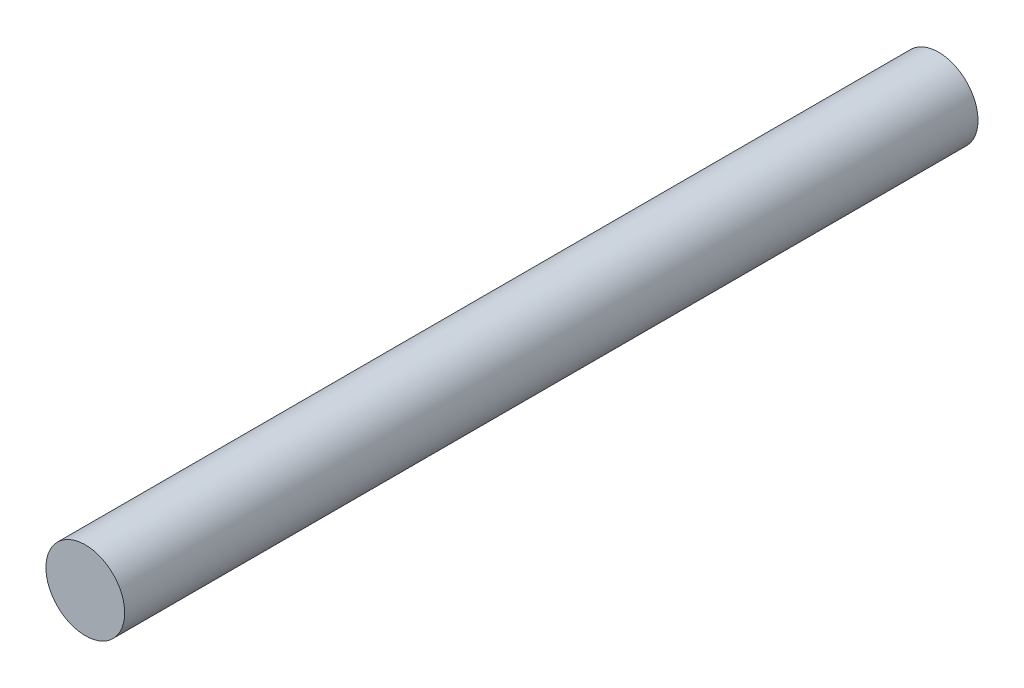
SolidWorks part; units mm, degrees
ref_plane "前视基准面" through (0, 0, 0) normal (0, 0, 1) x (1, 0, 0)
ref_plane "上视基准面" through (0, 0, 0) normal (0, 1, 0) x (1, 0, 0)
ref_plane "右视基准面" through (0, 0, 0) normal (1, 0, 0) x (0, 0, -1)
sketch "草图1" plane through (0, 0, 0) normal (0, 0, 1) x (1, 0, 0)
  circle A0 centre (0, 0) radius 1.5
  dimension "D1" = 3
extrude "凸台-拉伸1" add sketch "草图1" along normal mid plane 32.5
